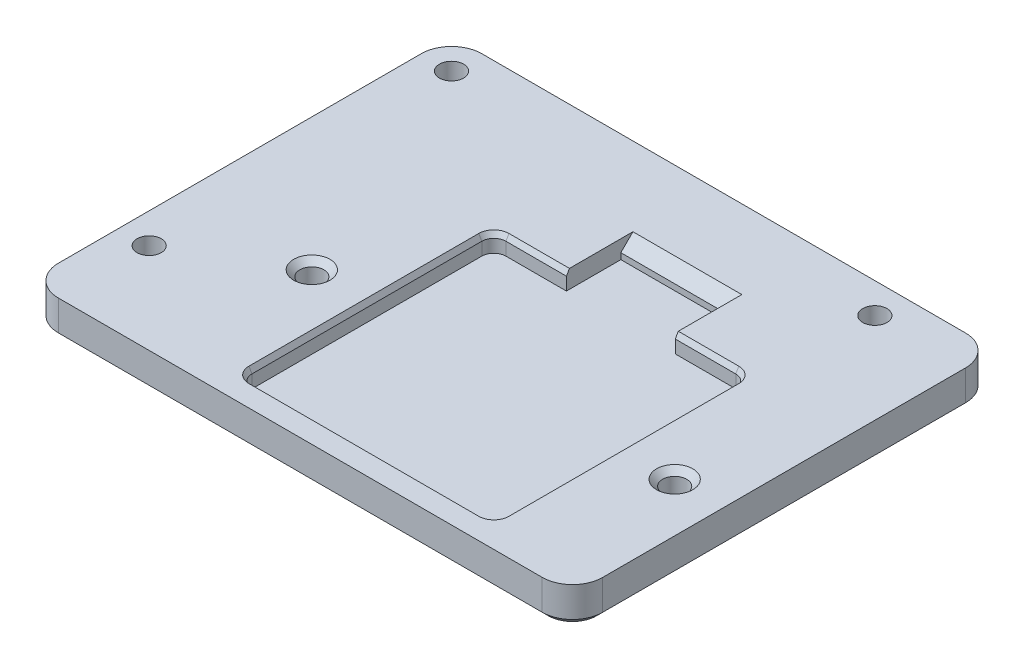
SolidWorks part; units mm, degrees
ref_plane "Спереди" through (0, 0, 0) normal (0, 0, 1) x (1, 0, 0)
ref_plane "Сверху" through (0, 0, 0) normal (0, 1, 0) x (1, 0, 0)
ref_plane "Справа" through (0, 0, 0) normal (1, 0, 0) x (0, 0, -1)
sketch "Эскиз1" plane through (0, 0, 0) normal (0, 1, 0) x (1, 0, 0)
  line L1 (-40, -40) -> (50, -40)
  line L2 (-40, -40) -> (-40, 30)
  line L3 (-40, 30) -> (50, 30)
  line L4 (50, -40) -> (50, 30)
  line L5 (5, 30) -> (5, -30) construction
  line L7 (-35, -25) -> (35, -25) construction
  line L8 (-35, -25) -> (-35, 25) construction
  line L9 (-35, 25) -> (35, 25) construction
  line L10 (35, -25) -> (35, 25) construction
  line L11 (0, 25) -> (0, -25) construction
  circle A0 centre (-35, 25) radius 2
  circle A1 centre (35, 25) radius 2
  circle A2 centre (-35, -25) radius 2
  circle A3 centre (35, -25) radius 2
  point P0 (0, 0)
  point P7 (0, 0)
  dimension "D3" = 4
  dimension "D4" = 70
  dimension "D1" = 90
  dimension "D2" = 70
  dimension "D5" = 50
  dimension "D6" = 50
extrude "Бобышка-Вытянуть1" add sketch "Эскиз1" along normal blind 6 contours L1 L4 L3 L2 A3 A2 A1 A0 | A3
fillet "Скругление1" radius 5 4 edges at (-40, 3, -30) (50, 3, -30) (50, 3, 40) (-40, 3, 40)
sketch "Эскиз2" plane through (0, 6, 0) normal (0, 1, 0) x (1, 0, 0)
  line L1 (-9, -36) -> (33, -36)
  line L2 (-9, -36) -> (-9, 6)
  line L3 (-9, 6) -> (33, 6)
  line L4 (33, -36) -> (33, 6)
  line L5 (12, 6) -> (12, -36) construction
  line L6 (-9, -15) -> (33, -15) construction
  circle A1 centre (35, 25) radius 2 construction
  circle A2 centre (-35, -25) radius 2 construction
  point P0 (12, -15)
  dimension "D2" = 40
  dimension "D3" = 23
  dimension "D4" = 47
  dimension "D5" = 10
  dimension "D1" = 42
extrude "Вырез-Вытянуть1" cut sketch "Эскиз2" against normal blind 3
fillet "Скругление2" radius 2 4 edges at (33, 4.5, 36) (-9, 4.5, 36) (-9, 4.5, -6) (33, 4.5, -6)
sketch "Эскиз4" plane through (0, 3, 0) normal (0, 1, 0) x (1, 0, 0)
  line L0 (11.9, 3.92) -> (11.9, -33.92) construction
  line L3 (11.9, -33.92) -> (33, -15) construction
  line L4 (33, -34) -> (33, 4) construction
  line L5 (33, -15) -> (-9.1, -15) construction
  circle A0 centre (11.9, -15) radius 5
  point P2 (0, 0)
extrude "Бобышка-Вытянуть2" [suppressed] add sketch "Эскиз4" along normal blind 100
sketch "Эскиз5" plane through (0, 6, 0) normal (0, 1, 0) x (1, 0, 0)
  line L0 (31, 6) -> (-7, 6) construction
  line L1 (3, -3) -> (21, -3)
  line L2 (3, -3) -> (3, 15)
  line L3 (3, 15) -> (21, 15)
  line L4 (21, -3) -> (21, 15)
  line L5 (12, 15) -> (12, -3) construction
  line L6 (3, 6) -> (21, 6) construction
  point P0 (12, 6)
  dimension "D1" = 18
  dimension "D2" = 18
extrude "Вырез-Вытянуть2" cut sketch "Эскиз5" against normal blind 3
chamfer "Фаска1" distance 2 angle 45 1 edges at (12, 6, -15)
chamfer "Фаска2" distance 1 angle 45 11 edges at (-38.5355, 0, 38.5355) (5, 0, 40) (48.5355, 0, 38.5355) (50, 0, 5) (48.5355, 0, -28.5355) (5, 0, -30) (-38.5355, 0, -28.5355) (-40, 0, 5) (-35, 0, -23) (35, 0, -23) (-35, 0, 27)
sketch "Эскиз6" plane through (0, 6, 0) normal (0, 1, 0) x (1, 0, 0)
  line L0 (-9, -15) -> (70.4184, -15) construction
  line L1 (-9, 4) -> (-9, -34) construction
  line L2 (70.4184, -15) -> (-44.4975, -15) construction
  line L3 (11.9, -15) -> (11.9, 19.6036) construction
  circle A0 centre (41.9, -15) radius 2
  circle A1 centre (-18.1, -15) radius 2
  dimension "D1" = 4
  dimension "D2" = 30
extrude "Вырез-Вытянуть3" cut sketch "Эскиз6" against normal blind 5
chamfer "Фаска3" distance 1 angle 45 2 edges at (41.9, 6, 17) (-18.1, 6, 13)
chamfer "Фаска4" distance 0.5 angle 60 9 edges at (-2, 6, -6) (-8.4142, 6, -5.4142) (-9, 6, 15) (-8.4142, 6, 35.4142) (12, 6, 36) (26, 6, -6) (32.4142, 6, 35.4142) (32.4142, 6, -5.4142) (33, 6, 15)
